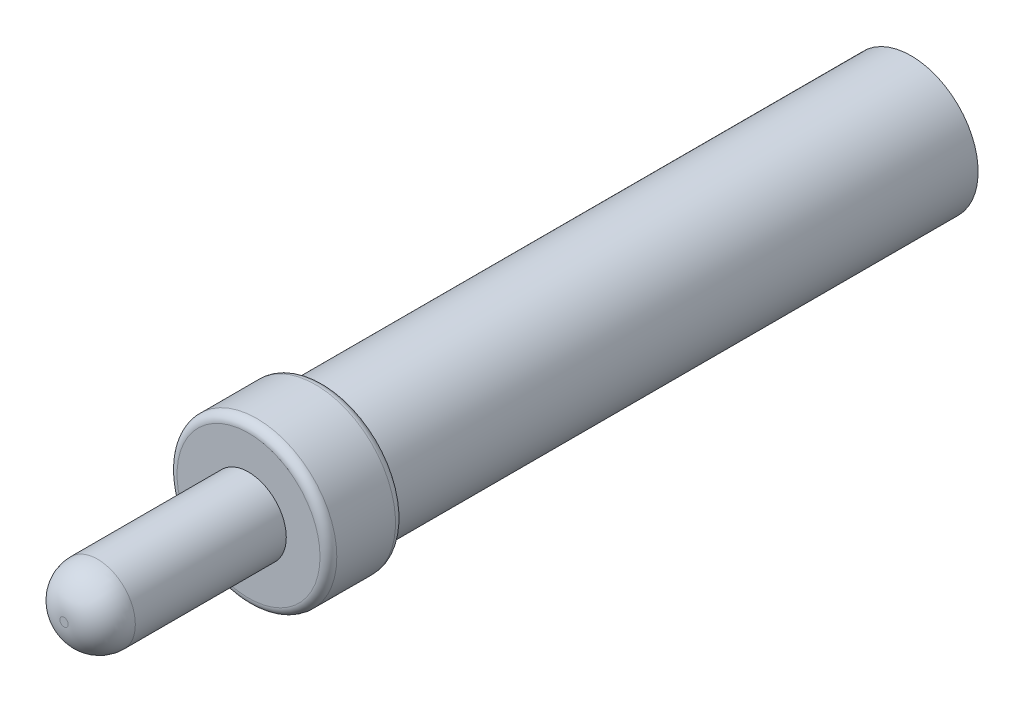
SolidWorks part; units mm, degrees
ref_plane "Plano frontal" through (0, 0, 0) normal (0, 0, 1) x (1, 0, 0)
ref_plane "Plano superior" through (0, 0, 0) normal (0, 1, 0) x (1, 0, 0)
ref_plane "Plano direito" through (0, 0, 0) normal (1, 0, 0) x (0, 0, -1)
sketch "Esboço1" plane through (0, 0, 0) normal (0, 0, 1) x (1, 0, 0)
  circle A0 centre (240.7084, 2.5961) radius 4.7625
  dimension "D1" = 9.525
extrude "Ressalto-extrusão1" add sketch "Esboço1" along normal blind 50.5
hole_wizard "Furo roscado de M3x0.52" positions "Esboço5" profile "Esboço4" tap size "M3x0.5" standard "Métrico Ansi"
sketch "Esboço5" plane through (0, 0, 0) normal (0, 0, -1) x (-1, 0, 0)
  point P0 (-240.7084, 2.5961)
sketch "Esboço4" plane through (240.7084, 2.5961, 0) normal (1, 0, 0) x (0, 1, 0)
  line L0 (0, 0) -> (0, 9.2511)
  line L1 (0, 9.2511) -> (1.25, 8.5)
  line L2 (1.25, 8.5) -> (1.25, 0)
  line L5 (1.25, 0) -> (0, 0)
  line L10 (0, 9.2511) -> (-1.25, 8.5) construction
  line L11 (0, -6.35) -> (0, 107.95) construction
  dimension "Tap Drill Dia." = 2.5
  dimension "Tap Drill Depth" = 8.5
  dimension "Drill Angle" = 118
cosmetic thread "Rosca de furo2" parameters "D1"=6, "D2"=3
cosmetic thread "Representação de rosca1" parameters "D1"=6, "D2"=3
sketch "Esboço8" plane through (0, 0, 0) normal (0, 0, -1) x (-1, 0, 0)
  circle A0 centre (-240.7084, 2.5961) radius 4
  dimension "D1" = 8
extrude "Corte-extrusão1" cut sketch "Esboço8" against normal blind 35 flip side to cut
sketch "Esboço10" plane through (0, 0, 50.5) normal (0, 0, 1) x (1, 0, 0)
  circle A0 centre (240.7084, 2.5961) radius 2.25
  dimension "D1" = 4.5
extrude "Corte-extrusão3" cut sketch "Esboço10" against normal blind 11 flip side to cut
fillet "Filete6" radius 2 1 edges at (242.9584, 2.5961, 50.5)
fillet "Filete5" radius 0.5 2 edges at (235.9459, 2.5961, 35) (245.4709, 2.5961, 39.5)
